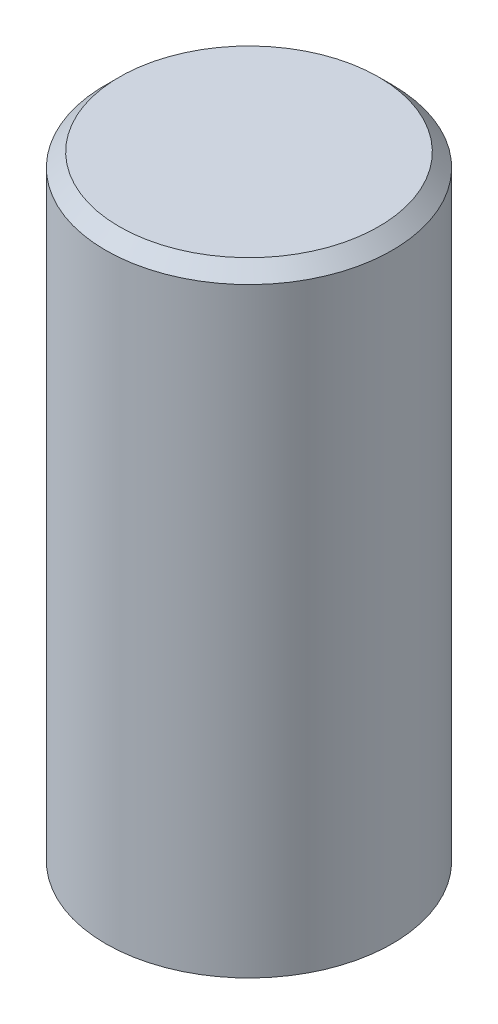
SolidWorks part; units mm, degrees
ref_plane "Front Plane" through (0, 0, 0) normal (0, 0, 1) x (1, 0, 0)
ref_plane "Top Plane" through (0, 0, 0) normal (0, 1, 0) x (1, 0, 0)
ref_plane "Right Plane" through (0, 0, 0) normal (1, 0, 0) x (0, 0, -1)
sketch "Sketch1" plane through (0, 0, 0) normal (0, 1, 0) x (1, 0, 0)
  circle A0 centre (0, 0) radius 21
  dimension "D1" = 42
extrude "Boss-Extrude1" add sketch "Sketch1" along normal blind 90
cosmetic thread "Cosmetic Thread2" parameters "D2"=37.066
chamfer "Chamfer1" distance 2 angle 45 1 edges at (0, 90, 21)
cosmetic thread "Cosmetic Thread1" parameters "D2"=37.066
